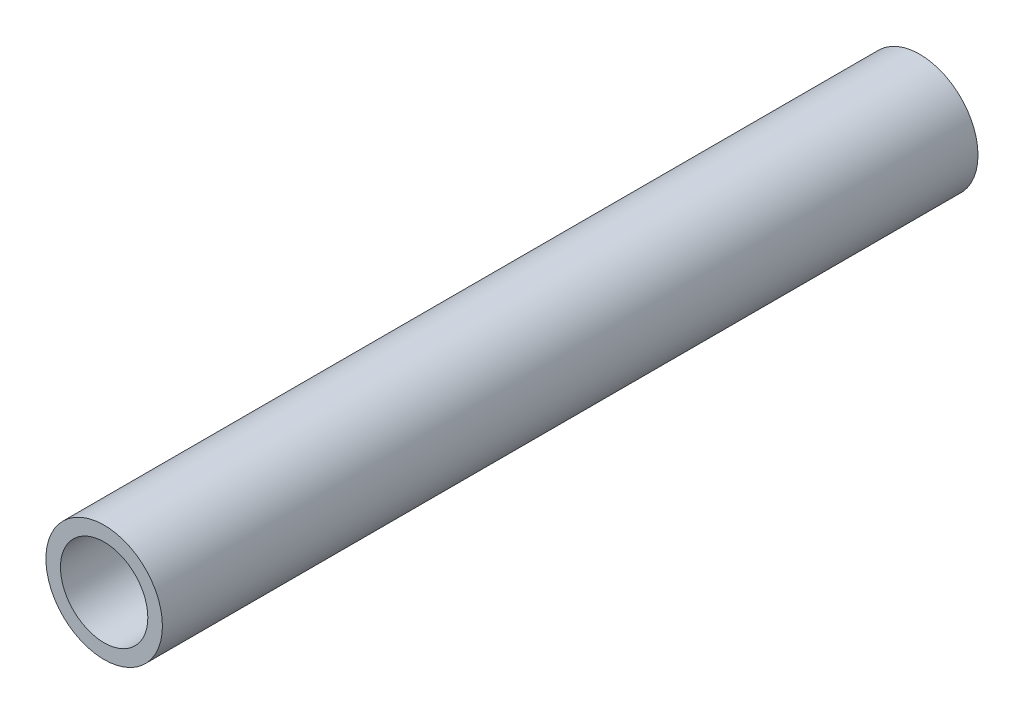
SolidWorks part; units mm, degrees
ref_plane "Front Plane" through (0, 0, 0) normal (0, 0, 1) x (1, 0, 0)
ref_plane "Top Plane" through (0, 0, 0) normal (0, 1, 0) x (1, 0, 0)
ref_plane "Right Plane" through (0, 0, 0) normal (1, 0, 0) x (0, 0, -1)
sketch "Sketch1" plane through (0, 0, 0) normal (0, 0, 1) x (1, 0, 0)
  circle A0 centre (0, 0) radius 9.525
  circle A1 centre (0, 0) radius 12.7
  dimension "D1" = 19.05
  dimension "D2" = 25.4
extrude "Boss-Extrude1" add sketch "Sketch1" along normal blind 177.8
